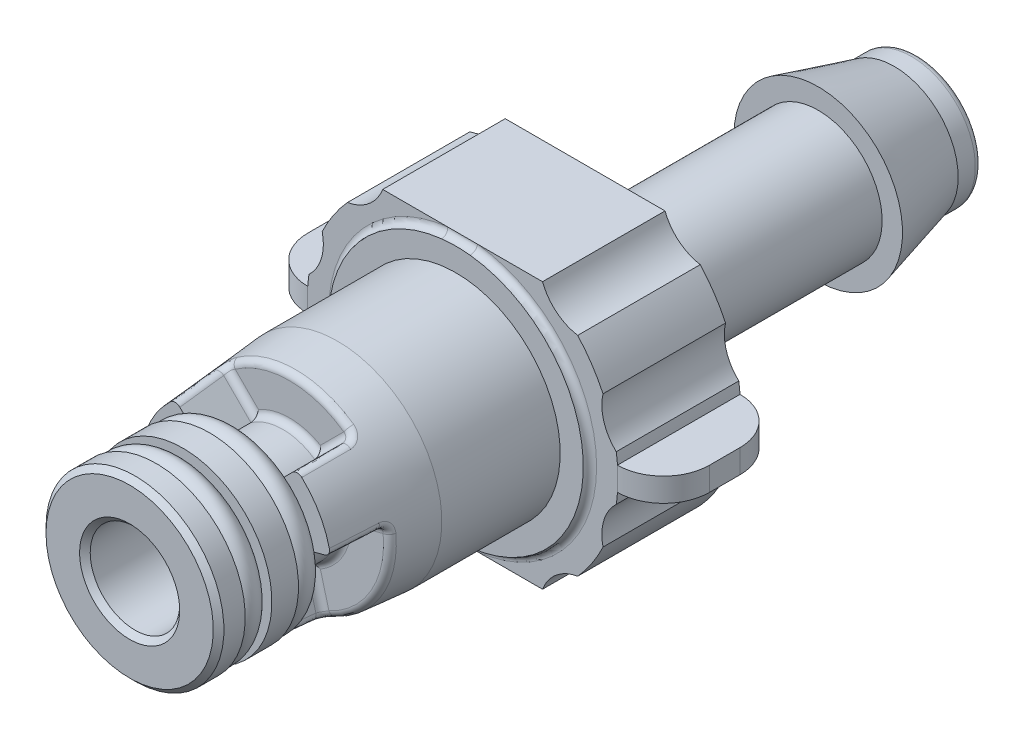
SolidWorks part; units mm, degrees
ref_plane "Front Plane" through (0, 0, 0) normal (0, 0, 1) x (1, 0, 0)
ref_plane "Top Plane" through (0, 0, 0) normal (0, 1, 0) x (1, 0, 0)
ref_plane "Right Plane" through (0, 0, 0) normal (1, 0, 0) x (0, 0, -1)
sketch "Sketch0" plane through (0, 0, 0) normal (0, 0, 1) x (1, 0, 0)
  line L0 (-3.81, 6.35) -> (3.81, 6.35) construction
  line L1 (3.81, 6.35) -> (3.81, -6.35) construction
  line L2 (3.81, -6.35) -> (-3.81, -6.35) construction
  line L3 (-3.81, -6.35) -> (-3.81, 6.35) construction
  circle A0 centre (0, 0) radius 7.4053 construction
  circle A1 centre (0, 0) radius 6.0724 construction
  circle A2 centre (0, 0) radius 3.048 construction
  circle A3 centre (0, 0) radius 2.1336 construction
  circle A4 centre (0, 0) radius 5.1615 construction
  circle A5 centre (0, 0) radius 8.1458 construction
  dimension "Body Minor D" = 12.1447
  dimension "Barb OD" = 6.096
  dimension "Barb ID" = 4.2672
  dimension "OD" = 14.8106
  dimension "Body ID" = 10.323
  dimension "Flange for NPT" = 16.2917
  dimension "Flat" = 12.7
  dimension "Flat W" = 7.62
sketch "Sketch1" plane through (0, 0, 0) normal (1, 0, 0) x (0, 0, -1)
  line L0 (0, 0) -> (15.875, 0) construction
  line L1 (0, 0) -> (-21.717, 0) construction
  point P3 (11.1125, 0)
  point P5 (-5.842, 0)
  point P6 (-12.1215, 0)
  point P7 (-3.7592, 0)
  dimension "D1" = 9.5955
  dimension "Barb or Thread Engagement" = 15.875
  dimension "OAL" = 37.592
  dimension "Hex 1 L" = 15.875
  dimension "D2" = 4.7625
  dimension "Body To Boss ID Transition Wall" = 3.7592
sketch "Sketch2" plane through (0, 0, 0) normal (0, 0, 1) x (1, 0, 0)
  line L0 (-3.81, 6.35) -> (3.81, 6.35) construction
  line L1 (3.81, -6.35) -> (-3.81, -6.35) construction
  line L2 (-3.81, 6.35) -> (3.81, 6.35)
  line L3 (3.81, -6.35) -> (-3.81, -6.35)
  line L4 (7.4053, 0) -> (0, 0) construction
  line L5 (5.8443, 7.1171) -> (5.4876, 4.9724) construction
  line L6 (5.4876, 4.9724) -> (6.6952, 3.1644) construction
  line L7 (7.3251, 1.0871) -> (7.3251, -1.0871) construction
  line L8 (0, 6.35) -> (0, -6.35) construction
  arc A0 (3.81, 6.35) -> (5.4876, 4.9724) centre (5.8443, 7.1171) ccw
  circle A1 centre (0, 0) radius 7.4053 construction
  arc A2 (6.6952, 3.1644) -> (7.3251, 1.0871) centre (8.8129, 2.6724) ccw
  arc A3 (7.3251, -1.0871) -> (6.6952, -3.1644) centre (8.8129, -2.6724) ccw
  arc A4 (5.4876, -4.9724) -> (3.81, -6.35) centre (5.8443, -7.1171) ccw
  circle A5 centre (0, 0) radius 7.035 construction
  arc A6 (5.4876, 4.9724) -> (6.6952, 3.1644) centre (0, 0) cw
  arc A7 (7.3251, -1.0871) -> (7.3251, 1.0871) centre (0, 0) ccw
  arc A8 (6.6952, -3.1644) -> (5.4876, -4.9724) centre (0, 0) cw
  arc A9 (-5.4876, -4.9724) -> (-3.81, -6.35) centre (-5.8443, -7.1171) cw
  arc A10 (-6.6952, -3.1644) -> (-5.4876, -4.9724) centre (0, 0) ccw
  arc A11 (-7.3251, -1.0871) -> (-6.6952, -3.1644) centre (-8.8129, -2.6724) cw
  arc A12 (-7.3251, -1.0871) -> (-7.3251, 1.0871) centre (0, 0) cw
  arc A13 (-6.6952, 3.1644) -> (-7.3251, 1.0871) centre (-8.8129, 2.6724) cw
  arc A14 (-5.4876, 4.9724) -> (-6.6952, 3.1644) centre (0, 0) ccw
  arc A15 (-3.81, 6.35) -> (-5.4876, 4.9724) centre (-5.8443, 7.1171) cw
  dimension "D1" = 14.0701
extrude "Body" add sketch "Sketch2" along normal up to vertex (21.717 mm away) up to point (0, 0, 21.717)
sketch "Sketch3" plane through (0, 0, 0) normal (0, 0, -1) x (-1, 0, 0)
  circle A1 centre (0, 0) radius 3.048 construction
  circle A2 centre (0, 0) radius 3.048
extrude "Boss-Extrude2" add sketch "Sketch3" along normal up to vertex (15.875 mm away) up to point (0, 0, -15.875)
sketch "Sketch5" plane through (0, 0, 0) normal (1, 0, 0) x (0, 0, -1)
  line L0 (-21.717, 6.35) -> (0, 6.35) construction
  line L1 (-12.1215, 6.6276) -> (-5.842, 6.6276) construction
  line L2 (-12.1215, 6.6276) -> (-12.1215, 6.0724)
  line L3 (-12.1215, 6.0724) -> (-5.842, 6.0724)
  line L4 (-5.842, 6.6276) -> (-5.842, 6.0724)
  line L5 (-12.1215, 6.6276) -> (-5.842, 6.0724) construction
  line L6 (-12.1215, 6.0724) -> (-5.842, 6.6276) construction
  line L7 (-12.1215, 6.0724) -> (0, 6.0724) construction
  line L10 (-5.842, 6.6276) -> (-5.842, 12.9072)
  line L11 (-5.842, 12.9072) -> (-12.1215, 12.9072)
  line L12 (-12.1215, 12.9072) -> (-12.1215, 6.6276)
  point P0 (-8.9818, 6.35)
revolve "Cut-Revolve1" cut sketch "Sketch5" angle 360 about L1
sketch "Sketch6" plane through (0, 0, -15.875) normal (0, 0, -1) x (-1, 0, 0)
  circle A0 centre (0, 0) radius 2.7432
  dimension "D1" = 5.4864
extrude "Barb End" add sketch "Sketch6" against normal up to vertex (4.7625 mm away) draft 15 up to point (0, 0, -11.1125) draft outward yes
sketch "Sketch7" plane through (0, 0, -15.875) normal (0, 0, -1) x (-1, 0, 0)
  circle A0 centre (0, 0) radius 2.1336 construction
  circle A1 centre (0, 0) radius 2.1336
extrude "Cut-Extrude1" cut sketch "Sketch7" against normal through all
sketch "Sketch11" plane through (0, 0, 0) normal (0, 0, -1) x (-1, 0, 0)
  line L0 (7.3251, 1.0871) -> (7.3251, -1.0871) construction
  line L1 (5.2311, 0.5618) -> (9.5795, 0.5618)
  line L2 (5.2311, 0.5618) -> (5.2311, -0.5618)
  line L3 (5.2311, -0.5618) -> (9.5795, -0.5618)
  line L4 (9.5795, 0.5618) -> (9.5795, -0.5618)
  line L5 (5.2311, 0.5618) -> (9.5795, -0.5618) construction
  line L6 (5.2311, -0.5618) -> (9.5795, 0.5618) construction
  line L7 (7.3251, -1.0871) -> (6.7323, -2.0415) construction
  line L8 (7.4053, 0) -> (9.5795, 0) construction
  circle A0 centre (0, 0) radius 7.4053 construction
  arc A1 (7.3251, -1.0871) -> (6.6952, -3.1644) centre (8.8129, -2.6724) ccw construction
  point P0 (7.4053, 0)
extrude "Boss-Extrude5" add sketch "Sketch11" against normal up to vertex (5.842 mm away) up to point (0, 0, 5.842)
sketch "Sketch12" plane through (0, 0.5618, 0) normal (0, 1, 0) x (1, 0, 0)
  line L0 (-9.5795, -5.842) -> (-9.5795, 0) construction
  line L1 (-9.5795, 0) -> (-7.384, 0) construction
  line L2 (-9.5795, -5.842) -> (-7.384, -5.842) construction
  line L3 (-9.5795, -2.1955) -> (-9.5795, -3.6465)
  line L4 (-7.384, 0) -> (-7.384, 2.1299)
  line L5 (-7.384, 2.1299) -> (-11.7094, 2.1299)
  line L6 (-11.7094, 2.1299) -> (-11.7094, -7.9719)
  line L7 (-11.7094, -7.9719) -> (-7.384, -7.9719)
  line L8 (-7.384, -7.9719) -> (-7.384, -5.842)
  line L9 (-9.5795, -2.921) -> (-11.7094, -2.921) construction
  arc A0 (-7.384, 0) -> (-9.5795, -2.1955) centre (-7.384, -2.1955) ccw
  arc A1 (-9.5795, -3.6465) -> (-7.384, -5.842) centre (-7.384, -3.6465) ccw
  dimension "D1" = 4.3254
extrude "Cut-Extrude3" cut sketch "Sketch12" against normal blind 33.4768
mirror "Mirror1" about plane through (0, 0, 0) normal (1, 0, 0) of "Boss-Extrude5", "Cut-Extrude3"
fillet "Fillet1" radius 0.635 1 edges at (-3.048, 0, 0)
fillet "Fillet3" radius 0.3175 3 edges at (-3.048, 0, -15.875) (0, 6.0724, 12.1215) (0, 6.0724, 5.842)
sketch "Sketch13" plane through (0, 0, 0) normal (1, 0, 0) x (0, 0, -1)
  line L0 (-6.1595, 6.0345) -> (-6.1595, 4.9724)
  line L1 (-6.1595, -6.0345) -> (-6.1595, 6.0345) construction
  line L2 (-6.1595, 4.9724) -> (-11.804, 4.9724)
  line L3 (-16.637, 4.5639) -> (-16.637, 2.9718)
  line L4 (-16.637, 2.9718) -> (-17.907, 2.9718)
  line L5 (-17.907, 2.9718) -> (-17.907, 4.2418)
  line L6 (-17.907, 4.2418) -> (-19.177, 4.2418)
  line L7 (-19.177, 4.2418) -> (-19.177, 2.9718)
  line L8 (-19.177, 2.9718) -> (-20.447, 2.9718)
  line L9 (-20.447, 2.9718) -> (-20.447, 4.2418)
  line L10 (-20.447, 4.2418) -> (-21.717, 4.2418)
  line L11 (-21.717, 4.9724) -> (-21.717, 3.1644) construction
  line L12 (-21.717, 4.2418) -> (-21.717, 6.35)
  line L13 (-21.717, 6.35) -> (-21.717, 8.4582)
  line L14 (-21.717, 8.4582) -> (-6.1595, 8.4582)
  line L15 (-6.1595, 8.4582) -> (-6.1595, 6.0345)
  line L16 (-11.804, 6.0345) -> (-11.804, -6.0345) construction
  line L17 (-11.804, 4.9724) -> (-16.637, 4.5639)
  line L18 (-20.447, 4.2418) -> (-16.637, 4.5639) construction
  line L19 (-5.842, 4.9724) -> (0, 4.9724) construction
  line L20 (0, 0) -> (-21.717, 0) construction
  line L21 (-21.717, 1.0871) -> (-21.717, -1.0871) construction
  line L22 (-20.447, 3.6068) -> (-20.3835, 3.6068) construction
  line L23 (-20.3835, 3.6068) -> (-19.2405, 3.6068) construction
  line L24 (-19.2405, 3.6068) -> (-19.177, 3.6068) construction
  line L25 (-19.177, 3.6068) -> (-17.907, 3.6068) construction
  line L26 (-17.907, 3.6068) -> (-17.8435, 3.6068) construction
  line L27 (-17.8435, 3.6068) -> (-16.7005, 3.6068) construction
  line L28 (-16.7005, 3.6068) -> (-16.637, 3.6068) construction
  line L30 (-21.717, 4.2418) -> (-21.717, 2.1336) construction
  circle A0 centre (-17.272, 3.6068) radius 0.5715
  circle A1 centre (-19.812, 3.6068) radius 0.5715
  dimension "D1" = 1.143
  dimension "O-Rings" = 1.27
revolve "Cut-Revolve2" cut sketch "Sketch13" angle 360 about L20
sketch "Sketch14" plane through (0, 0, 16.637) normal (0, 0, 1) x (1, 0, 0)
  line L0 (-4.5639, 0) -> (-1.5213, 0) construction
  line L1 (-1.5213, 0) -> (1.5213, 0) construction
  line L2 (1.5213, 0) -> (4.5639, 0) construction
  line L3 (-1.5213, 4.3029) -> (-1.5213, 2.1514) construction
  line L4 (1.5213, -4.3029) -> (-1.5213, -4.3029) construction
  line L5 (1.5213, -4.3029) -> (1.5213, 4.3029) construction
  line L6 (1.5213, 4.3029) -> (-1.5213, 4.3029) construction
  line L7 (-1.5213, -4.3029) -> (-1.5213, 4.3029) construction
  line L8 (1.5213, -4.3029) -> (-1.5213, 4.3029) construction
  line L9 (1.5213, 4.3029) -> (-1.5213, -4.3029) construction
  line L10 (-1.5213, 2.1514) -> (-1.5213, 0) construction
  line L11 (-1.5213, 2.1514) -> (-2.8967, 3.5268)
  line L12 (-2.8967, 3.5268) -> (2.8967, 3.5268) construction
  line L13 (2.8967, 3.5268) -> (1.5213, 2.1514)
  line L14 (-2.8967, 3.5268) -> (-4.272, 4.9022)
  line L15 (2.8967, 3.5268) -> (4.272, 4.9022)
  circle A0 centre (0, 0) radius 4.5639 construction
  arc A1 (-1.5213, 2.1514) -> (1.5213, 2.1514) centre (0, 0) cw
  arc A2 (-2.8967, 3.5268) -> (2.8967, 3.5268) centre (0, 0) cw construction
  circle A3 centre (0, 0) radius 2.1336 construction
  arc A4 (-4.272, 4.9022) -> (4.272, 4.9022) centre (0, 0) cw
  point P8 (0, 0)
  dimension "D1" = 90
extrude "Cut-Extrude4" cut sketch "Sketch14" against normal blind 2.54
pattern_circular "CirPattern1" count 3 over 360 about axis through (0, 0, -15.875) along (0, 0, 1) of "Cut-Extrude4"
fillet "Fillet4" radius 0.3175 18 edges at (-4.1384, -2.3893, 14.097) (-3.6674, 0.5214, 14.097) (-2.2819, -1.3175, 14.097) (-1.3822, -3.4368, 14.097) (4.1384, -2.3893, 14.097) (1.3822, -3.4368, 14.097) (2.2819, -1.3175, 14.097) (3.6674, 0.5214, 14.097) (0, 4.7786, 14.097) (2.2852, 2.9154, 14.097) (0, 2.6349, 14.097) (-2.2852, 2.9154, 14.097)
chamfer "Chamfer1" distance 0.254 angle 45 2 edges at (-2.1336, 0, 21.717) (-4.2418, 0, 21.717)
equation "\"Flat W@Sketch0\"=\"Flat@Sketch0\"*.6"
equation "\"Barb ID@Sketch0\"=\"Barb OD@Sketch0\"*.7"
equation "\"D1@Sketch2\" = \"OD@Sketch0\" *.95"
equation "\"Body Minor D@Sketch0\" = \"OD@Sketch0\"*.82"
equation "\"Body ID@Sketch0\" = \"Body Minor D@Sketch0\"*.85"
equation "\"D1@Sketch6\" = \"Barb OD@Sketch0\"*.9"
equation "\"Body To Boss ID Transition Wall@Sketch1\" = \"OAL@Sketch1\"*.1"
equation "\"D1@Fillet1\" = \"Flat@Sketch0\"/20"
equation "\"D1@Fillet3\" = \"Flat@Sketch0\"/40"
equation "\"Flange for NPT@Sketch0\" = \"OD@Sketch0\" *1.1"
equation "\"D2@Sketch1\" = \"Barb or Thread Engagement@Sketch1\"*.3"
equation "\"D1@Sketch13\" = \"O-Rings@Sketch13\"*.9"
